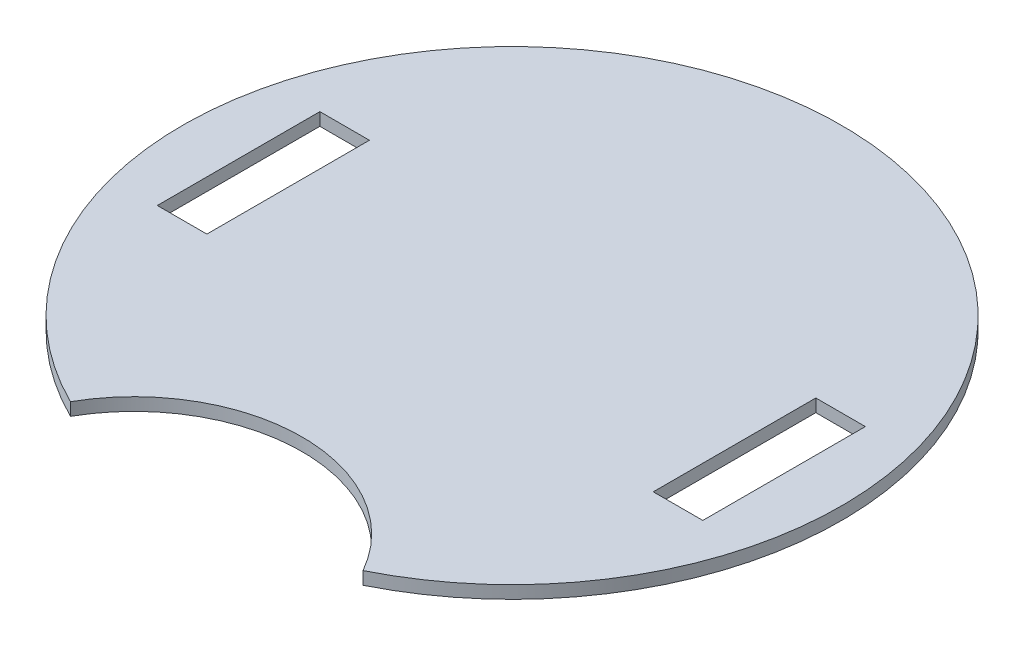
SolidWorks part; units mm, degrees
ref_plane "Front Plane" through (0, 0, 0) normal (0, 0, 1) x (1, 0, 0)
ref_plane "Top Plane" through (0, 0, 0) normal (0, 1, 0) x (1, 0, 0)
ref_plane "Right Plane" through (0, 0, 0) normal (1, 0, 0) x (0, 0, -1)
sketch "Sketch1" plane through (0, 0, 0) normal (0, 1, 0) x (1, 0, 0)
  line L0 (0, -86.0416) -> (-33.2911, -67.2064) construction
  line L1 (0, -86.0416) -> (0, 0) construction
  arc A0 (33.2911, -67.2064) -> (-33.2911, -67.2064) centre (0, 0) ccw
  arc A1 (33.2911, -67.2064) -> (-33.2911, -67.2064) centre (0, -86.0416) ccw
  dimension "D1" = 150
  dimension "D2" = 76.5
  dimension "D3" = 60.5
extrude "Boss-Extrude1" add sketch "Sketch1" along normal blind 2.9
sketch "solenoid placement" plane through (0, 2.9, 0) normal (0, 1, 0) x (1, 0, 0)
  line L0 (0, 0) -> (0, -36) construction
  line L1 (0, -36) -> (0, -47.7916) construction
  line L2 (-19, -36) -> (19, -36)
  line L3 (-19, -36) -> (-19, 28.4)
  line L4 (-19, 28.4) -> (19, 28.4)
  line L5 (19, -36) -> (19, 28.4)
  circle A1 centre (0, 0) radius 75 construction
  arc A2 (33.2911, -67.2064) -> (-33.2911, -67.2064) centre (0, 0) ccw construction
  arc A3 (33.2911, -67.2064) -> (-33.2911, -67.2064) centre (0, -86.0416) ccw construction
  dimension "D1" = 64.4
  dimension "D2" = 36
  dimension "D4" = 38
sketch "Sketch2" plane through (0, 2.9, 0) normal (0, 1, 0) x (1, 0, 0)
  line L1 (-61.7709, 18.03) -> (-51.0952, 18.03) construction
  line L2 (-61.7709, 18.03) -> (-61.7709, -18.3617) construction
  line L3 (-61.7709, -18.3617) -> (-51.0952, -18.3617) construction
  line L4 (-51.0952, 18.03) -> (-51.0952, -18.3617) construction
  line L8 (-62.0709, -18.6617) -> (-50.7952, -18.6617)
  line L9 (-50.7952, 18.33) -> (-50.7952, -18.6617)
  line L10 (-62.0709, 18.33) -> (-50.7952, 18.33)
  line L11 (-62.0709, 18.33) -> (-62.0709, -18.6617)
  line L12 (0, 0) -> (0, 75) construction
  line L13 (51.0952, 18.03) -> (51.0952, -18.3617) construction
  line L14 (61.7709, -18.3617) -> (51.0952, -18.3617) construction
  line L15 (61.7709, 18.03) -> (61.7709, -18.3617) construction
  line L16 (61.7709, 18.03) -> (51.0952, 18.03) construction
  line L17 (62.0709, 18.33) -> (62.0709, -18.6617)
  line L18 (62.0709, 18.33) -> (50.7952, 18.33)
  line L19 (50.7952, 18.33) -> (50.7952, -18.6617)
  line L20 (62.0709, -18.6617) -> (50.7952, -18.6617)
  arc A0 (33.2911, -67.2064) -> (-33.2911, -67.2064) centre (0, 0) ccw construction
  dimension "D1" = 0.3
extrude "Cut-Extrude1" cut sketch "Sketch2" against normal through all
equation "\"smallPulleyTeeth\"= 15"
equation "\"largePulleyTeeth\"= 30"
equation "\"eighthThick\"= 2.9mm"
equation "\"sixteenthThick\" = 1.7mm"
equation "\"wheelEighthThick\"=3.0mm"
equation "\"quarterThick\"=5.6mm"
equation "\"OD\" = 150mm"
equation "\"puckAngle\" = 60.5deg"
equation "\"D1@Sketch1\"=\"OD\""
equation "\"puckDiam\" = 76.5mm"
equation "\"D2@Sketch1\"=\"puckDiam\""
equation "\"D3@Sketch1\"=\"puckAngle\""
equation "\"D1@Boss-Extrude1\"=\"eighthThick\""
equation "\"axlePress\" = 5.8mm"
equation "\"press\" = 0.3mm"
equation "\"wheelClear\" = 0.3mm"
equation "\"D1@Sketch2\"=\"wheelClear\""
